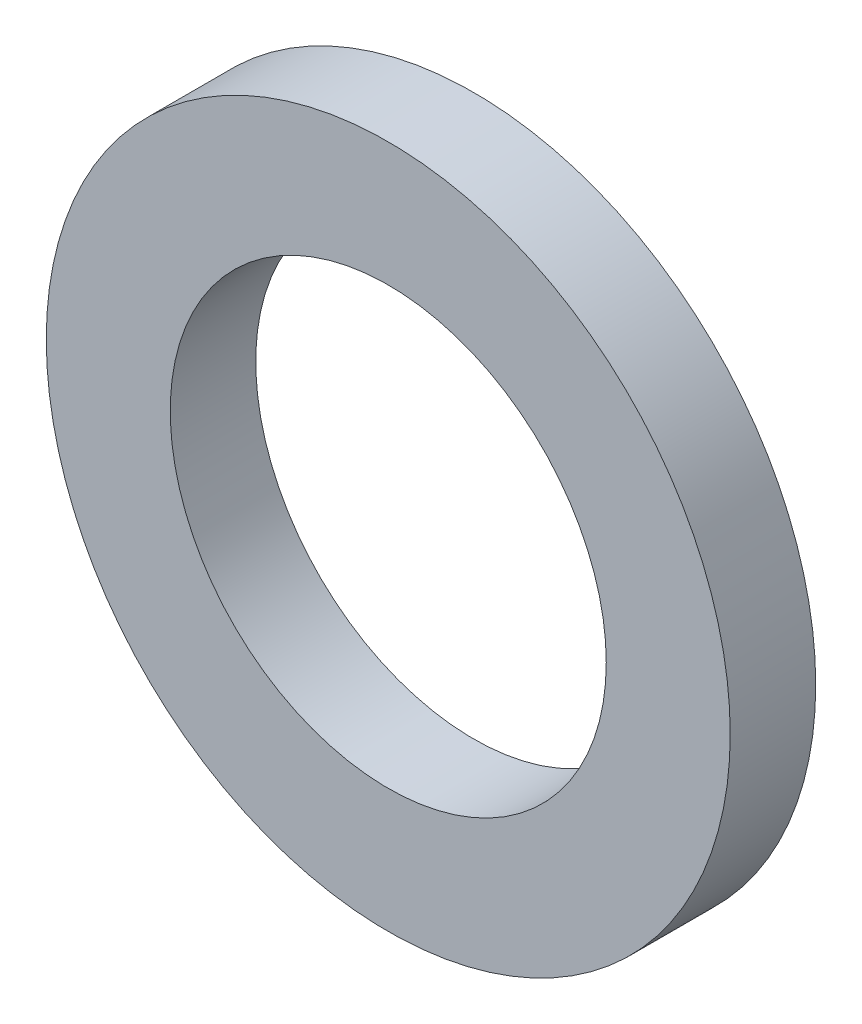
SolidWorks part; units mm, degrees
ref_plane "Plan1" through (0, 0, 0) normal (0, 0, 1) x (1, 0, 0)
ref_plane "Plan2" through (0, 0, 0) normal (0, 1, 0) x (1, 0, 0)
ref_plane "Plan3" through (0, 0, 0) normal (1, 0, 0) x (0, 0, -1)
sketch "Esquisse1" plane through (0, 0, 0) normal (0, 0, 1) x (1, 0, 0)
  circle A0 centre (0, 0) radius 5.1
  circle A1 centre (0, 0) radius 8
  dimension "D1" = 10.2
  dimension "D2" = 16
extrude "Base-Extrusion" add sketch "Esquisse1" along normal blind 2
